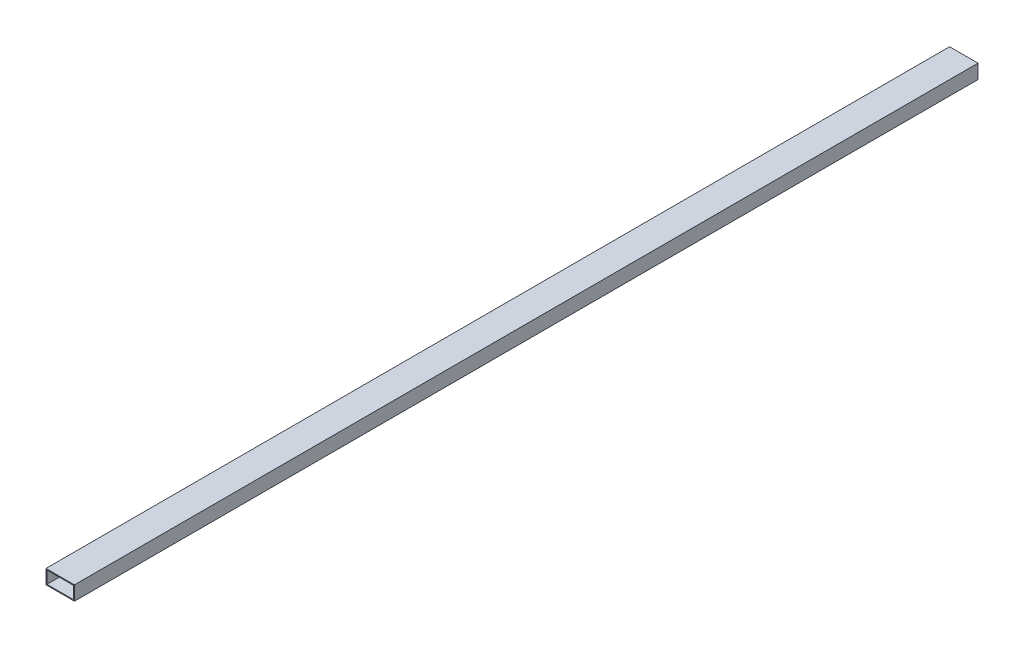
SolidWorks part; units mm, degrees
material "1100-H18 棒材(SS)"
ref_plane "前视基准面" through (0, 0, 0) normal (0, 0, 1) x (1, 0, 0)
ref_plane "上视基准面" through (0, 0, 0) normal (0, 1, 0) x (1, 0, 0)
ref_plane "右视基准面" through (0, 0, 0) normal (1, 0, 0) x (0, 0, -1)
other "Configuration Table"
sketch "草图1" plane through (0, 0, 0) normal (0, 0, 1) x (1, 0, 0)
  line L1 (0, 0) -> (30, 0)
  line L2 (0, 0) -> (0, 15)
  line L3 (0, 15) -> (30, 15)
  line L4 (30, 0) -> (30, 15)
  line L5 (1, 1) -> (29, 1)
  line L6 (1, 1) -> (1, 14)
  line L7 (1, 14) -> (29, 14)
  line L8 (29, 1) -> (29, 14)
  dimension "D1" = 30
  dimension "D2" = 15
  dimension "D3" = 1
  dimension "D4" = 1
  dimension "D5" = 1
  dimension "D6" = 1
extrude "凸台-拉伸1" add sketch "草图1" along normal blind 953
